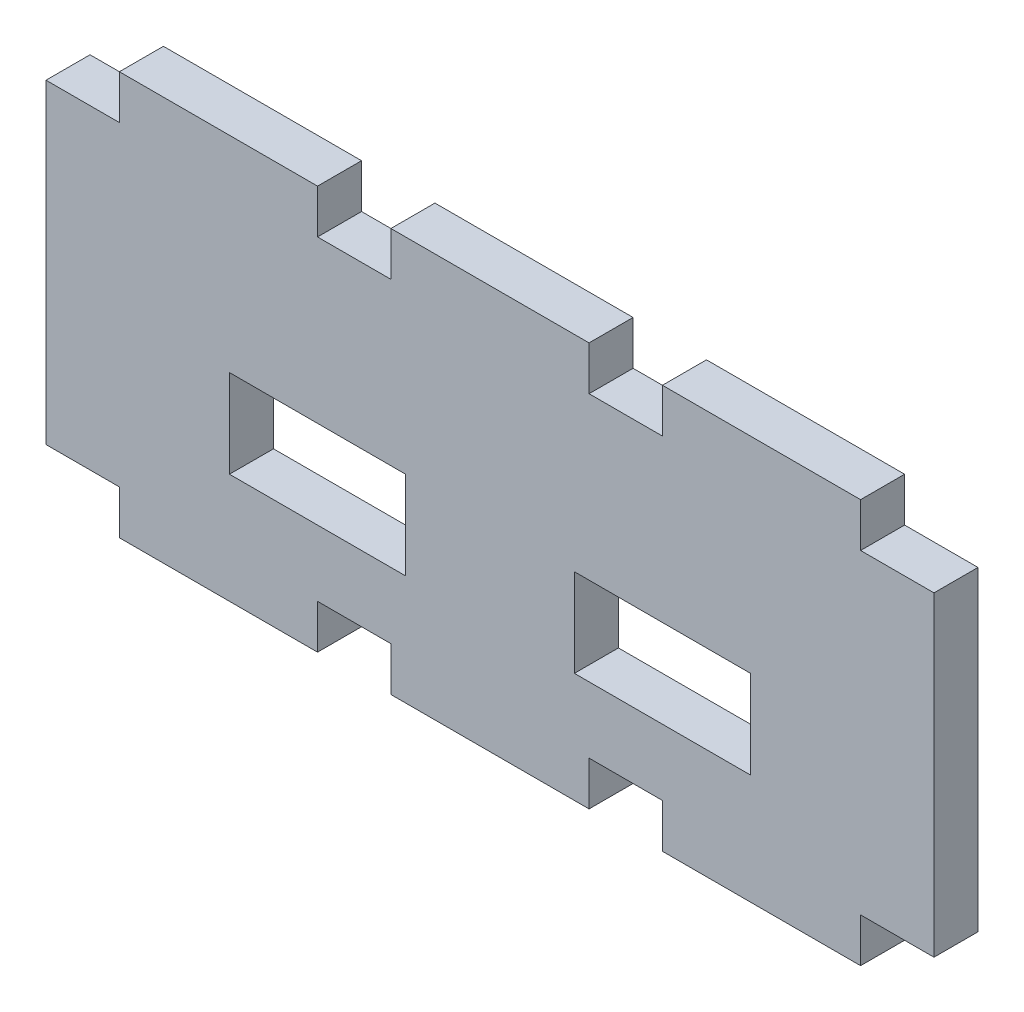
SolidWorks part; units mm, degrees
ref_plane "Plan de face" through (0, 0, 0) normal (0, 0, 1) x (1, 0, 0)
ref_plane "Plan de dessus" through (0, 0, 0) normal (0, 1, 0) x (1, 0, 0)
ref_plane "Plan de droite" through (0, 0, 0) normal (1, 0, 0) x (0, 0, -1)
sketch "Esquisse1" plane through (0, 0, 0) normal (0, 0, 1) x (1, 0, 0)
  line L1 (0, 0) -> (-121, 0)
  line L2 (0, 0) -> (0, 55)
  line L3 (0, 55) -> (-121, 55)
  line L4 (-121, 0) -> (-121, 55)
  dimension "D1" = 55
  dimension "D2" = 121
extrude "Boss.-Extru.1" add sketch "Esquisse1" along normal blind 6
sketch "Esquisse2" plane through (0, 0, 6) normal (0, 0, 1) x (1, 0, 0)
  line L0 (0, 55) -> (-121, 55) construction
  line L1 (-121, 55) -> (-111, 55)
  line L2 (-121, 55) -> (-121, 49)
  line L3 (-121, 49) -> (-111, 49)
  line L4 (-111, 55) -> (-111, 49)
  line L5 (-84, 55) -> (-74, 55)
  line L6 (-84, 55) -> (-84, 49)
  line L7 (-84, 49) -> (-74, 49)
  line L8 (-74, 55) -> (-74, 49)
  line L10 (-121, 0) -> (0, 0) construction
  line L11 (-47, 55) -> (-37, 55)
  line L12 (-47, 55) -> (-47, 49)
  line L13 (-47, 49) -> (-37, 49)
  line L14 (0, 55) -> (-10, 55)
  line L15 (0, 55) -> (0, 49)
  line L16 (0, 49) -> (-10, 49)
  line L17 (-10, 55) -> (-10, 49)
  line L18 (-121, 0) -> (-111, 0)
  line L19 (-121, 0) -> (-121, 6)
  line L20 (-121, 6) -> (-111, 6)
  line L21 (-111, 0) -> (-111, 6)
  line L23 (-84, 0) -> (-74, 0)
  line L24 (-84, 0) -> (-84, 6)
  line L25 (-84, 6) -> (-74, 6)
  line L26 (-37, 55) -> (-37, 49)
  line L27 (-47, 0) -> (-37, 0)
  line L28 (-47, 0) -> (-47, 6)
  line L29 (-47, 6) -> (-37, 6)
  line L30 (-37, 0) -> (-37, 6)
  line L31 (0, 0) -> (-10, 0)
  line L32 (0, 0) -> (0, 6)
  line L33 (0, 6) -> (-10, 6)
  line L34 (-10, 0) -> (-10, 6)
  line L35 (-74, 0) -> (-74, 6)
  dimension "D1" = 10
  dimension "D3" = 10
  dimension "D4" = 6
  dimension "D5" = 10
  dimension "D6" = 27
  dimension "D7" = 10
  dimension "D8" = 27
  dimension "D9" = 10
  dimension "D10" = 27
  dimension "D11" = 10
  dimension "D12" = 27
  dimension "D13" = 6
  dimension "D14" = 6
  dimension "D15" = 6
  dimension "D16" = 6
  dimension "D17" = 6
  dimension "D18" = 27
  dimension "D19" = 6
  dimension "D20" = 6
  dimension "D21" = 27
extrude "Enlèv. mat encoche" cut sketch "Esquisse2" against normal through all
sketch "Esquisse3" plane through (0, 0, 6) normal (0, 0, 1) x (1, 0, 0)
  line L0 (-121, 49) -> (-121, 6) construction
  line L1 (-96, 27) -> (-72, 27)
  line L2 (-96, 27) -> (-96, 15)
  line L3 (-96, 15) -> (-72, 15)
  line L4 (-72, 27) -> (-72, 15)
  line L5 (-49, 27) -> (-25, 27)
  line L6 (-49, 27) -> (-49, 15)
  line L7 (-49, 15) -> (-25, 15)
  line L8 (-25, 27) -> (-25, 15)
  line L11 (-84, 55) -> (-111, 55) construction
  line L13 (-47, 55) -> (-74, 55) construction
  dimension "D1" = 12
  dimension "D2" = 24
  dimension "D3" = 24
  dimension "D4" = 12
  dimension "D5" = 25
  dimension "D6" = 23
  dimension "D7" = 40
  dimension "D8" = 40
extrude "Enlèv. mat.-Extru.2" cut sketch "Esquisse3" against normal blind 6
